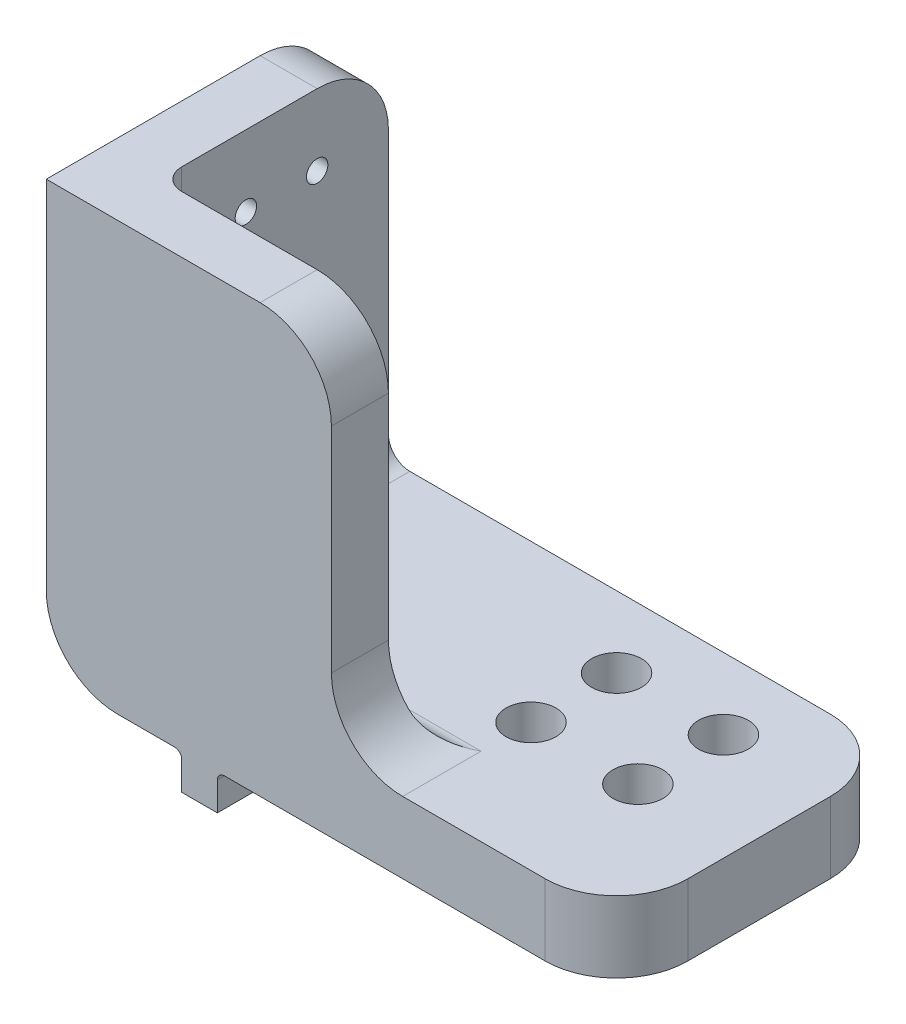
SolidWorks part; units mm, degrees
ref_plane "Front Plane" through (0, 0, 0) normal (0, 0, 1) x (1, 0, 0)
ref_plane "Top Plane" through (0, 0, 0) normal (0, 1, 0) x (1, 0, 0)
ref_plane "Right Plane" through (0, 0, 0) normal (1, 0, 0) x (0, 0, -1)
sketch "Sketch1" plane through (0, 0, 0) normal (0, 1, 0) x (1, 0, 0)
  line L0 (80, 20) -> (0, 20) construction
  line L1 (0, 0) -> (80, 0)
  line L2 (0, 0) -> (0, 40)
  line L3 (0, 40) -> (80, 40)
  line L4 (80, 0) -> (80, 40)
  line L5 (0, 30) -> (80, 30) construction
  line L7 (0, 18) -> (80, 18) construction
  circle A2 centre (65, 30) radius 1.6
  circle A3 centre (50, 30) radius 1.6
  circle A6 centre (50, 18) radius 1.6
  circle A7 centre (65, 18) radius 1.6
  dimension "D3" = 10
  dimension "D4" = 18
  dimension "D5" = 15
  dimension "D7" = 3.2
  dimension "D1" = 40
  dimension "D2" = 80
  dimension "15" = 15
extrude "Boss-Extrude1" add sketch "Sketch1" along normal blind 10
sketch "Sketch2" plane through (0, 10, 0) normal (0, 1, 0) x (1, 0, 0)
  line L0 (80, 40) -> (0, 40) construction
  line L1 (0, 0) -> (8, 0)
  line L2 (0, 0) -> (0, 40)
  line L3 (0, 40) -> (8, 40)
  line L4 (8, 0) -> (8, 40)
  line L6 (0, 0) -> (40, 0)
  line L7 (0, 0) -> (0, 8)
  line L8 (0, 8) -> (40, 8)
  line L9 (40, 0) -> (40, 8)
  line M4 (0, 40) -> (0, 0)
  line M5 (0, 0) -> (80, 0)
  line M7 (80, 40) -> (0, 40)
  dimension "D1" = 8
  dimension "D2" = 8
  dimension "D3" = 40
extrude "Boss-Extrude2" add sketch "Sketch2" along normal blind 50 contours L8 L4 M4 M7 | L8 L2 L4 M5 | L9 L8 L4 M5
fillet "Fillet1" radius 10 5 edges at (4, 60, -40) (40, 60, -4) (80, 5, -40) (80, 5, 0) (40, 10, -4)
fillet "Fillet2" radius 3 3 edges at (8, 10, -24) (29, 10, -8) (8, 35, -8)
sketch "Sketch3" plane through (0, 10, 0) normal (0, 1, 0) x (1, 0, 0)
  circle A0 centre (50, 30) radius 3.5
  circle A1 centre (50, 18) radius 3.5
  circle A2 centre (65, 18) radius 3.5
  circle A3 centre (65, 30) radius 3.5
  dimension "D1" = 7
extrude "Cut-Extrude1" cut sketch "Sketch3" against normal blind 5
fillet "Fillet3" radius 10 1 edges at (0, 0, -20)
sketch "Sketch4" plane through (0, 0, 0) normal (0, -1, 0) x (1, 0, 0)
  line L0 (10, 0) -> (70, 0) construction
  line L1 (19, 0) -> (24, 0)
  line L2 (19, 0) -> (19, -40)
  line L3 (19, -40) -> (24, -40)
  line L4 (24, 0) -> (24, -40)
  line L5 (70, -40) -> (10, -40) construction
  line L7 (0, -40) -> (0, 0) construction
  dimension "D1" = 24
  dimension "D2" = 5
extrude "Boss-Extrude3" add sketch "Sketch4" along normal blind 5
fillet "Fillet4" radius 1 2 edges at (24, 0, -20) (19, 0, -20)
sketch "Sketch5" plane through (0, 0, 0) normal (-1, 0, 0) x (0, 0, 1)
  line L0 (-30, 60) -> (-30, 50) construction
  line L1 (-30, 50) -> (-40, 50) construction
  line L2 (-30, 50) -> (-20, 50) construction
  circle A0 centre (-30, 50) radius 1.5
  circle A1 centre (-20, 50) radius 1.5
  dimension "D1" = 3
  dimension "D2" = 10
extrude "Cut-Extrude2" cut sketch "Sketch5" against normal blind 80
